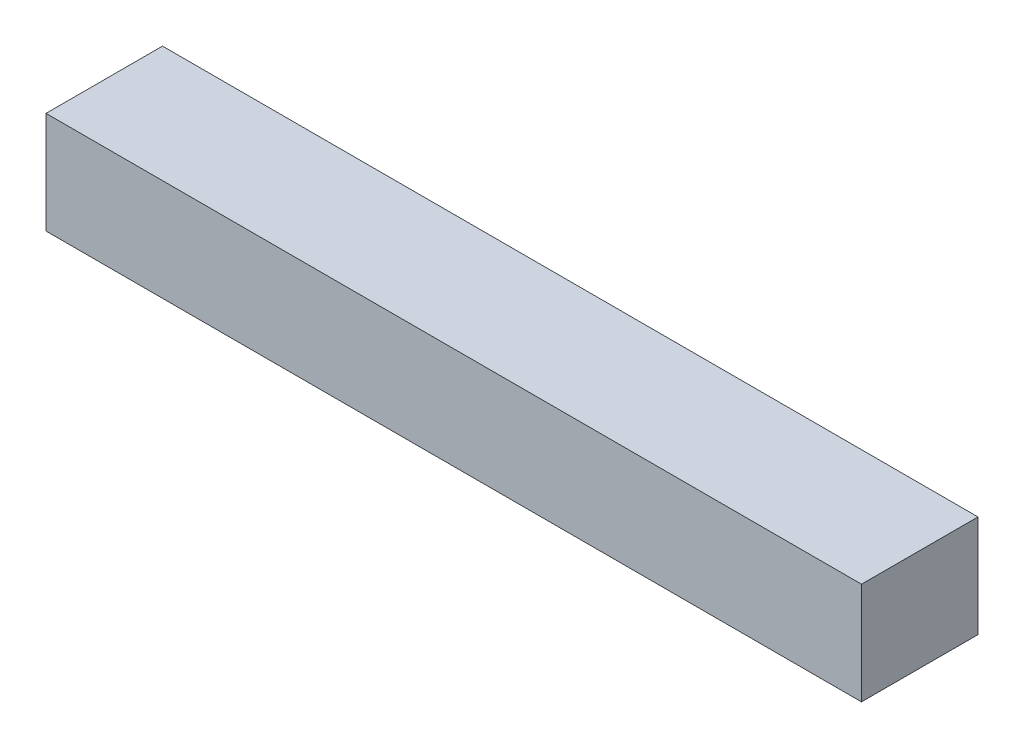
SolidWorks part; units mm, degrees
material "AISI 4130 Steel, normalized at 870C"
ref_plane "Front Plane" through (0, 0, 0) normal (0, 0, 1) x (1, 0, 0)
ref_plane "Top Plane" through (0, 0, 0) normal (0, 1, 0) x (1, 0, 0)
ref_plane "Right Plane" through (0, 0, 0) normal (1, 0, 0) x (0, 0, -1)
sketch "Sketch1" plane through (0, 0, 0) normal (1, 0, 0) x (0, 0, -1)
  line L1 (-7.6704, -4.0496) -> (-15.6704, -4.0496)
  line L2 (-7.6704, -4.0496) -> (-7.6704, -11.0496)
  line L3 (-7.6704, -11.0496) -> (-15.6704, -11.0496)
  line L4 (-15.6704, -4.0496) -> (-15.6704, -11.0496)
extrude "Boss-Extrude1" add sketch "Sketch1" along normal blind 56
scale "Escala1" scale about centroid uniform scaling yes scale factor 0.5
